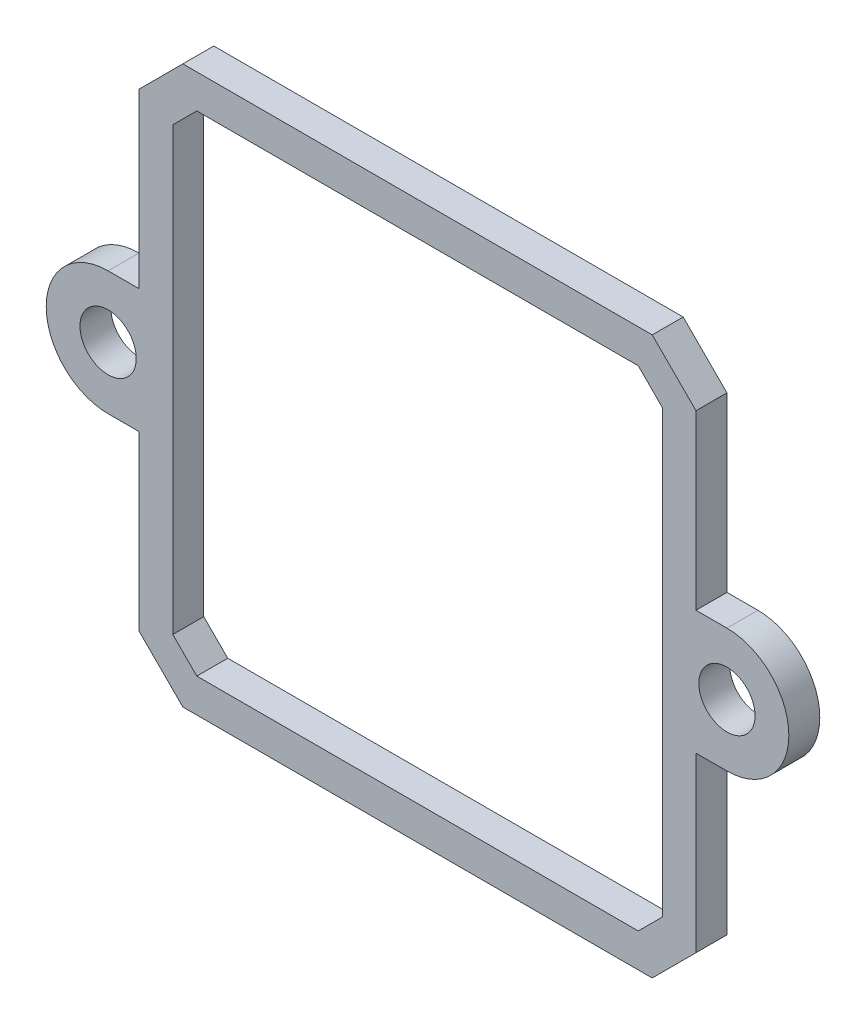
SolidWorks part; units mm, degrees
ref_plane "Front" through (0, 0, 0) normal (0, 0, 1) x (1, 0, 0)
ref_plane "Top" through (0, 0, 0) normal (0, 1, 0) x (1, 0, 0)
ref_plane "Right" through (0, 0, 0) normal (1, 0, 0) x (0, 0, -1)
sketch "Sketch1" plane through (0, 0, 0) normal (0, 0, 1) x (1, 0, 0)
  line L0 (-9.9, 8.3434) -> (-8.3434, 9.9)
  line L1 (-9.9, 9.9) -> (9.9, 9.9)
  line L2 (-9.9, 9.9) -> (-9.9, -9.9)
  line L3 (-9.9, -9.9) -> (9.9, -9.9)
  line L4 (9.9, 9.9) -> (9.9, -9.9)
  line L5 (8.3434, 9.9) -> (9.9, 8.3434)
  line L6 (-9.9, -8.3434) -> (-8.3434, -9.9)
  line L7 (8.3434, -9.9) -> (9.9, -8.3434)
  line L8 (9.9, 2.2) -> (11, 2.2)
  line L9 (9.9, -2.2) -> (11, -2.2)
  line L10 (-9.9, 2.2) -> (-11, 2.2)
  line L11 (-9.9, -2.2) -> (-11, -2.2)
  line L12 (-8.7, 7.8463) -> (-8.7, -7.8463)
  line L13 (-8.7, -7.8463) -> (-7.8463, -8.7)
  line L14 (-7.8463, -8.7) -> (7.8463, -8.7)
  line L15 (7.8463, -8.7) -> (8.7, -7.8463)
  line L16 (8.7, -7.8463) -> (8.7, 7.8463)
  line L17 (8.7, 7.8463) -> (7.8463, 8.7)
  line L18 (7.8463, 8.7) -> (-7.8463, 8.7)
  line L19 (-7.8463, 8.7) -> (-8.7, 7.8463)
  arc A0 (11, 2.2) -> (11, -2.2) centre (11, 0) cw
  arc A1 (-11, -2.2) -> (-11, 2.2) centre (-11, 0) cw
  circle A2 centre (-11, 0) radius 1
  circle A3 centre (11, 0) radius 1
  point P4 (0, 9.9)
  point P5 (9.9, 0)
  dimension "D4" = 2.2
  dimension "D5" = 2.2
  dimension "D7" = 2
  dimension "D8" = 2
  dimension "D1" = 25.8
  dimension "D2" = 19.8
  dimension "D3" = 19.8
  dimension "D6" = 11
  dimension "D9" = 11
  dimension "D10" = 1.2
  dimension "D11" = 1.2
  dimension "D12" = 1.2
  dimension "D13" = 1.2
  dimension "D14" = 1.2
  dimension "D15" = 1.2
  dimension "D16" = 1.2
  dimension "D17" = 1.2
extrude "Boss-Extrude1" add sketch "Sketch1" along normal blind 1.1 contours L3 L7 L4 L5 L1 L0 L2 L6 L19 L18 L17 L16 L15 L14 L13 L12 | A1 L11 L2 L10 A2 | A0 L8 L4 L9 A3
